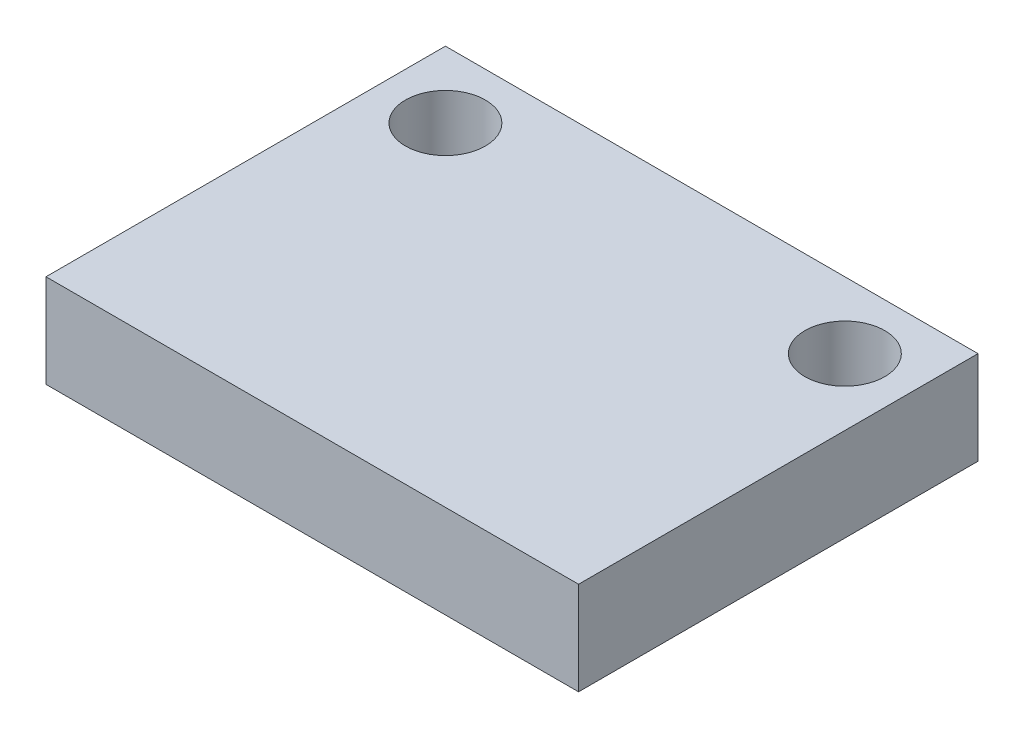
SolidWorks part; units mm, degrees
ref_plane "Front Plane" through (0, 0, 0) normal (0, 0, 1) x (1, 0, 0)
ref_plane "Top Plane" through (0, 0, 0) normal (0, 1, 0) x (1, 0, 0)
ref_plane "Right Plane" through (0, 0, 0) normal (1, 0, 0) x (0, 0, -1)
sketch "Sketch1" plane through (0, 0, 0) normal (0, 1, 0) x (1, 0, 0)
  line L0 (10, 0) -> (10, 24.1247) construction
  line L1 (0, 0) -> (20, 0)
  line L2 (0, 0) -> (0, 15)
  line L3 (0, 15) -> (20, 15)
  line L4 (20, 0) -> (20, 15)
  line L5 (2.5, 12.5) -> (2.5, 14)
  line L6 (2.5, 12.5) -> (1, 12.5)
  circle A0 centre (2.5, 12.5) radius 1.5
  circle A1 centre (17.5, 12.5) radius 1.5
  point P12 (2.5, 12.5)
  dimension "D3" = 3
  dimension "D1" = 20
  dimension "D2" = 15
  dimension "D4" = 1
  dimension "D5" = 1
extrude "Boss-Extrude1" add sketch "Sketch1" along normal blind 3.5 contours L0 L1 L4 L3 A1 | L1 L0 L3 L2 A0
